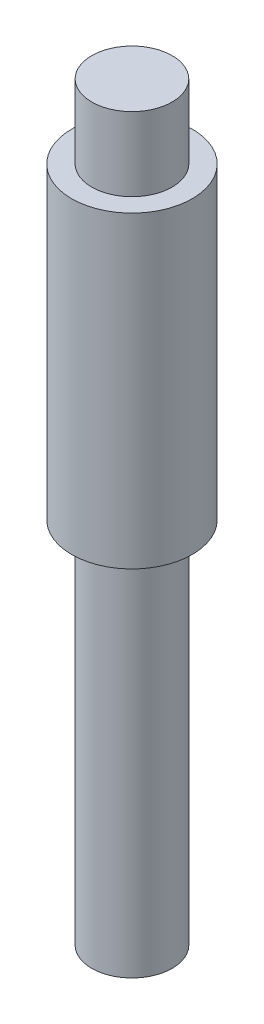
SolidWorks part; units mm, degrees
material "6061-T6 (SS)"
ref_plane "Front Plane" through (0, 0, 0) normal (0, 0, 1) x (1, 0, 0)
ref_plane "Top Plane" through (0, 0, 0) normal (0, 1, 0) x (1, 0, 0)
ref_plane "Right Plane" through (0, 0, 0) normal (1, 0, 0) x (0, 0, -1)
sketch "Sketch1" plane through (0, 0, 0) normal (0, 1, 0) x (1, 0, 0)
  circle A0 centre (0, 0) radius 1.5
  dimension "D1" = 3
extrude "Boss-Extrude1" add sketch "Sketch1" against normal blind 13.75
sketch "Sketch2" plane through (0, 0, 0) normal (0, 1, 0) x (1, 0, 0)
  circle A0 centre (0, 0) radius 2.25
  dimension "D1" = 4.5
extrude "Boss-Extrude2" add sketch "Sketch2" along normal blind 11.5
sketch "Sketch3" plane through (0, 11.5, 0) normal (0, 1, 0) x (1, 0, 0)
  circle A0 centre (0, 0) radius 1.5
  dimension "D1" = 3
extrude "Boss-Extrude3" add sketch "Sketch3" along normal blind 2.75
